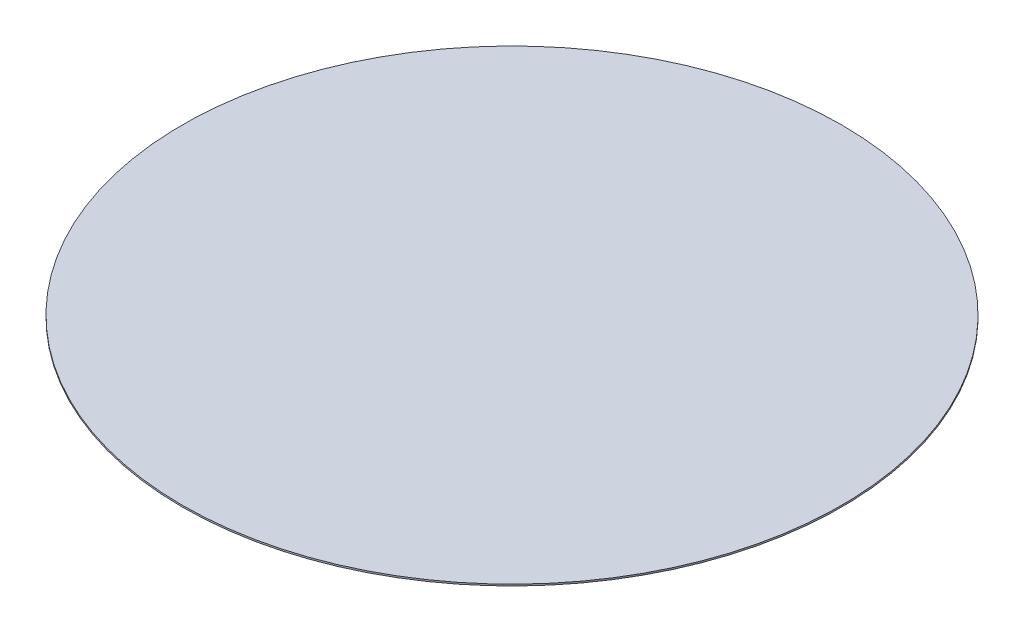
SolidWorks part; units mm, degrees
ref_plane "Front" through (0, 0, 0) normal (0, 0, 1) x (1, 0, 0)
ref_plane "Top" through (0, 0, 0) normal (0, 1, 0) x (1, 0, 0)
ref_plane "Right" through (0, 0, 0) normal (1, 0, 0) x (0, 0, -1)
sketch "Sketch1" plane through (0, 0, 0) normal (0, 1, 0) x (1, 0, 0)
  circle A0 centre (0, 0) radius 10.25
  dimension "D1" = 20.5
extrude "Boss-Extrude1" add sketch "Sketch1" along normal blind 0.05
